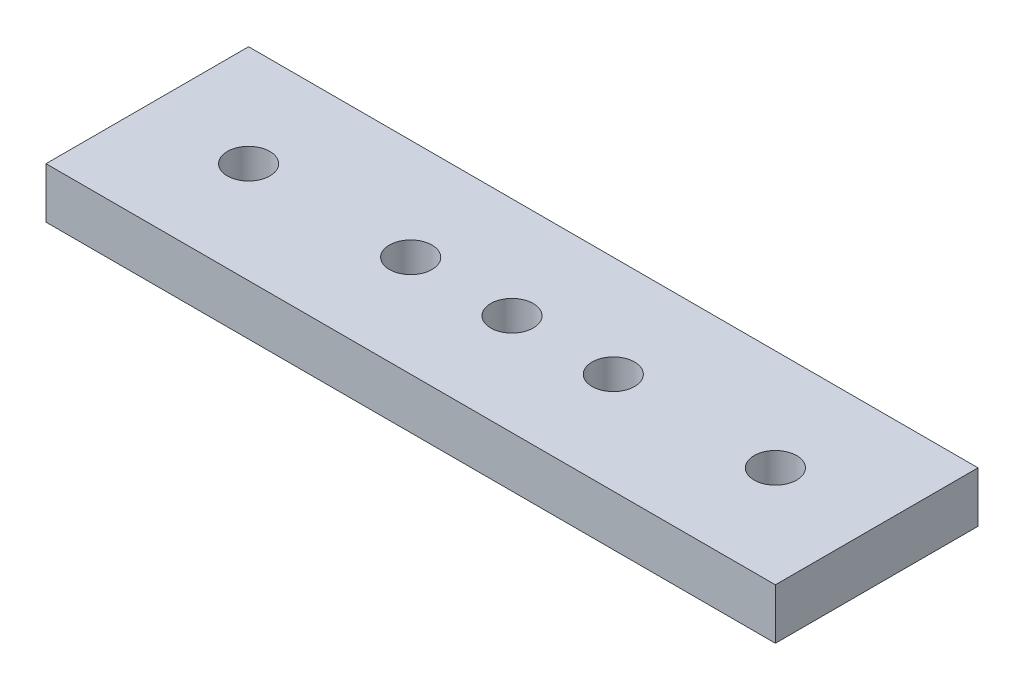
SolidWorks part; units mm, degrees
ref_plane "前视基准面" through (0, 0, 0) normal (0, 0, 1) x (1, 0, 0)
ref_plane "上视基准面" through (0, 0, 0) normal (0, 1, 0) x (1, 0, 0)
ref_plane "右视基准面" through (0, 0, 0) normal (1, 0, 0) x (0, 0, -1)
ref_plane "基准面4" through (0, -5, 0) normal (0, -1, 0) x (1, 0, 0)
sketch "草图1" plane through (0, -5, 0) normal (0, -1, 0) x (1, 0, 0)
  line L0 (36, 0) -> (36, 20)
  line L1 (36, 20) -> (-36, 20)
  line L2 (-36, 20) -> (-36, 0)
  line L3 (-36, 0) -> (36, 0)
  circle A0 centre (10, 10) radius 2.1
  circle A1 centre (26, 10) radius 2.1
  circle A2 centre (-10, 10) radius 2.1
  circle A3 centre (-26, 10) radius 2.1
  circle A4 centre (0, 10) radius 2.1
extrude "凸台-拉伸1" add sketch "草图1" against normal blind 5
